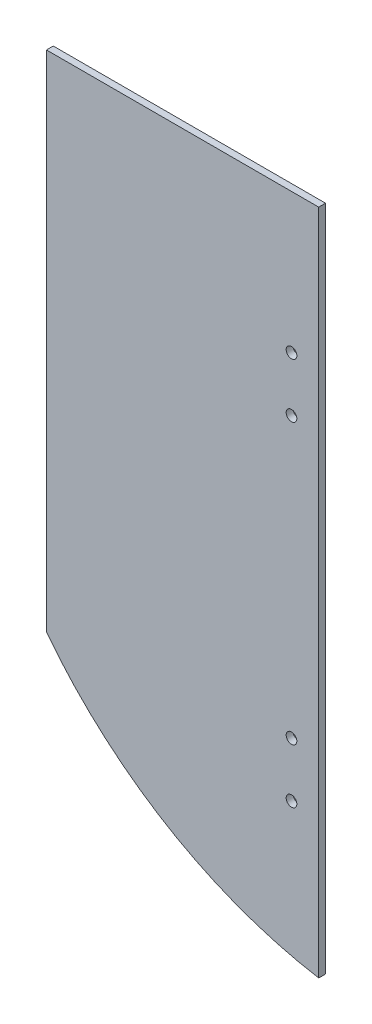
SolidWorks part; units mm, degrees
ref_plane "Front Plane" through (0, 0, 0) normal (1, 0, 0) x (0, 1, 0)
ref_plane "Top Plane" through (0, 0, 0) normal (0, 0, 1) x (0, 1, 0)
ref_plane "Right Plane" through (0, 0, 0) normal (0, 1, 0) x (-1, 0, 0)
sketch "Sketch1" plane through (0, 0, 0) normal (0, 0, 1) x (0, 1, 0)
  line L1 (-155.702, -63.5) -> (155.702, -63.5)
  line L2 (-155.702, -63.5) -> (-155.702, 63.5)
  line L3 (-155.702, 63.5) -> (155.702, 63.5)
  line L4 (155.702, -63.5) -> (155.702, 63.5)
  line L5 (-155.702, -63.5) -> (155.702, 63.5) construction
  line L6 (-155.702, 63.5) -> (155.702, -63.5) construction
  point P1 (0, 0)
  dimension "D1" = 311.404
  dimension "D2" = 127
extrude "Boss-Extrude1" add sketch "Sketch1" along normal blind 3.175
sketch "Sketch2" plane through (0, 0, 3.175) normal (0, 0, 1) x (1, 0, 0)
  line L0 (50.8, 155.702) -> (50.8, -155.702) construction
  line L1 (63.5, 155.702) -> (-63.5, 155.702) construction
  line L2 (-63.5, -155.702) -> (63.5, -155.702) construction
  line L4 (50.8, -155.702) -> (50.8, -90.551) construction
  line L5 (50.8, -65.151) -> (50.8, 0) construction
  line L6 (50.8, 0) -> (50.8, 65.151) construction
  line L7 (50.8, 90.551) -> (50.8, 155.702) construction
  line L8 (63.5, -155.702) -> (63.5, 155.702) construction
  point P8 (50.8, -90.551)
  point P9 (50.8, -65.151)
  point P10 (50.8, 65.151)
  point P11 (50.8, 90.551)
  dimension "D1" = 12.7
  dimension "D2" = 25.4
  dimension "D3" = 25.4
hole_wizard "#9 (0.196) Diameter Hole1" positions "Sketch2" profile "Sketch3" hole size "#9" standard "ANSI Inch" end condition through all
sketch "Sketch3" plane through (50.8, 90.551, 3.175) normal (1, 0, 0) x (0, -1, 0)
  line L0 (0, 0) -> (0, 3.175)
  line L1 (0, 3.175) -> (2.4892, 3.175)
  line L2 (2.4892, 3.175) -> (2.4892, 0)
  line L5 (2.4892, 0) -> (0, 0)
  line L11 (0, -6.35) -> (0, 107.95) construction
  dimension "Thru Hole Dia." = 4.9784
  dimension "Thru Hole Depth" = 3.175
sketch "Sketch4" plane through (0, 0, 3.175) normal (0, 0, 1) x (1, 0, 0)
  line L0 (-63.5, 155.702) -> (-63.5, -155.702) construction
  line L1 (-63.5, -155.702) -> (63.5, -155.702) construction
  line L2 (-63.5, -79.502) -> (-63.5, -155.702)
  line L3 (-63.5, -155.702) -> (63.5, -155.702)
  arc A0 (-63.5, -79.502) -> (63.5, -155.702) centre (97.3558, 44.6577) ccw
  dimension "D1" = 203.2
  dimension "D2" = 76.2
extrude "Cut-Extrude1" cut sketch "Sketch4" against normal through all
